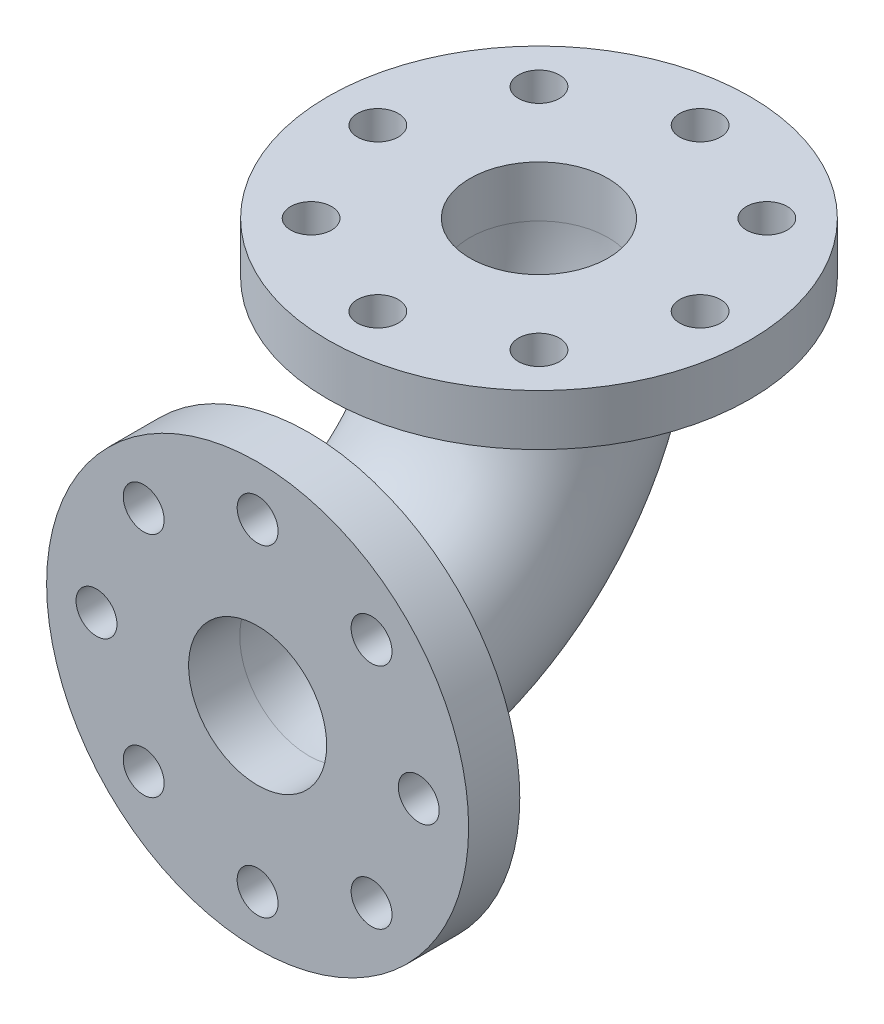
SolidWorks part; units mm, degrees
ref_plane "Ön Düzlem" through (0, 0, 0) normal (0, 0, 1) x (1, 0, 0)
ref_plane "Üst Düzlem" through (0, 0, 0) normal (0, 1, 0) x (1, 0, 0)
ref_plane "Sağ Düzlem" through (0, 0, 0) normal (1, 0, 0) x (0, 0, -1)
sketch "Çizim2" plane through (0, 0, 0) normal (0, 0, 1) x (1, 0, 0)
  circle A0 centre (0, 0) radius 82.5
  circle A1 centre (0, 0) radius 27
  dimension "D1" = 165
  dimension "D2" = 54
extrude "Yükseklik-Ekstrüzyon1" add sketch "Çizim2" along normal blind 20
sketch "Çizim3" plane through (0, 0, 20) normal (0, 0, 1) x (1, 0, 0)
  circle A0 centre (0, 0) radius 63 construction
  circle A1 centre (0, 63) radius 8
  circle A2 centre (0, 0) radius 63 construction
  circle A3 centre (44.5477, 44.5477) radius 8
  circle A4 centre (0, 0) radius 63 construction
  circle A5 centre (63, 0) radius 8
  circle A6 centre (0, 0) radius 63 construction
  circle A7 centre (44.5477, -44.5477) radius 8
  circle A8 centre (0, 0) radius 63 construction
  circle A9 centre (0, -63) radius 8
  circle A10 centre (0, 0) radius 63 construction
  circle A11 centre (-44.5477, -44.5477) radius 8
  circle A12 centre (0, 0) radius 63 construction
  circle A13 centre (-63, 0) radius 8
  circle A14 centre (0, 0) radius 63 construction
  circle A15 centre (-44.5477, 44.5477) radius 8
  point P29 (0, 0)
  dimension "D1" = 126
  dimension "D2" = 8
extrude "Kes-Ekstrüzyon1" cut sketch "Çizim3" against normal blind 20
sketch "Çizim4" plane through (0, 0, 0) normal (0, 0, -1) x (-1, 0, 0)
  circle A0 centre (0, 0) radius 27
  circle A1 centre (0, 0) radius 43
sketch "Çizim5" plane through (0, 0, 0) normal (1, 0, 0) x (0, 0, -1)
  arc A0 (0, 0) -> (90, 90) centre (0, 90) ccw
  dimension "D1" = 90
  dimension "D2" = 90
  dimension "D3" = 90
sweep "Süpür1" add profiles "Çizim4" path "Çizim5"
ref_plane "Düzlem1" through (0, 45, -45) normal (0, -0.7071, 0.7071) x (-1, 0, 0)
mirror "Aynalama3" about plane through (0, 45, -45) normal (0, -0.7071, 0.7071) of "Kes-Ekstrüzyon1", "Yükseklik-Ekstrüzyon1"
